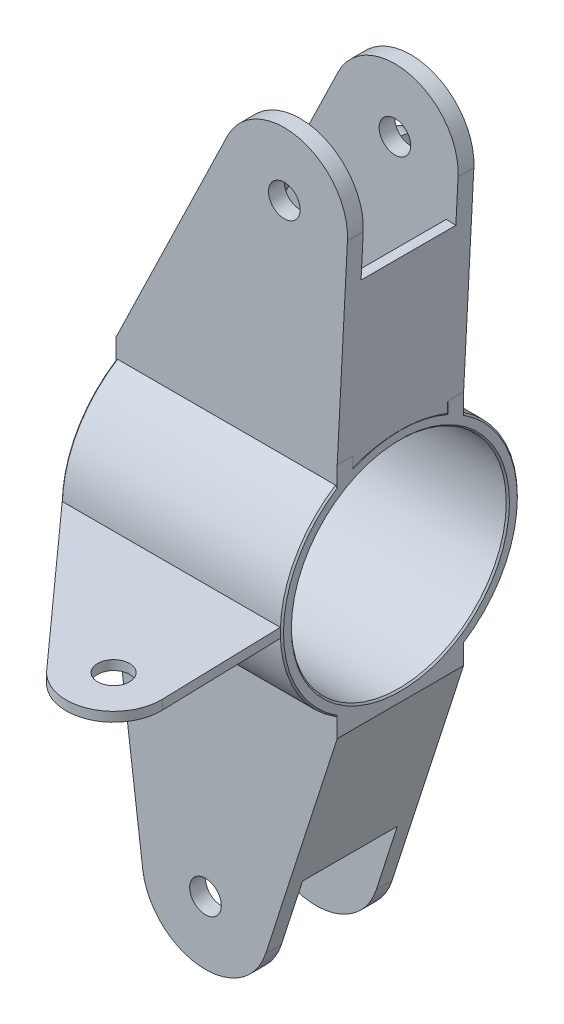
SolidWorks part; units mm, degrees
ref_plane "Front Plane" through (0, 0, 0) normal (0, 0, 1) x (1, 0, 0)
ref_plane "Top Plane" through (0, 0, 0) normal (0, 1, 0) x (1, 0, 0)
ref_plane "Right Plane" through (0, 0, 0) normal (1, 0, 0) x (0, 0, -1)
sketch "Sketch1" plane through (0, 0, 0) normal (1, 0, 0) x (0, 0, -1)
  circle A0 centre (0, 0) radius 34.007
  circle A1 centre (0, 0) radius 37.5
  dimension "D1" = 68.014
  dimension "D2" = 75
extrude "Boss-Extrude1" add sketch "Sketch1" along normal mid plane 70
sketch "Sketch4" plane through (0, 0, 0) normal (0, 0, 1) x (1, 0, 0)
  line L0 (-35, 0) -> (5.8, 0) construction
  line L1 (-35, 37.5) -> (-35, -37.5) construction
  line L2 (5.8, 101.6) -> (5.8, -101.6) construction
  line L3 (18.2749, 101.6) -> (-6.6749, -101.6) construction
  line L4 (0.2757, 110.3193) -> (-35, 37.5)
  line L5 (35, 37.5) -> (38.2484, 100.5713)
  line L6 (-35, -37.5) -> (-26.5147, -104.1267)
  line L7 (35, -37.5) -> (12.3606, -107.7358)
  line L8 (-35, -37.5) -> (35, -37.5) construction
  line L9 (-35, -37.5) -> (35, -37.5)
  line L10 (35, 37.5) -> (-35, 37.5) construction
  line L11 (35, 37.5) -> (-35, 37.5)
  circle A0 centre (18.2749, 101.6) radius 5.007
  circle A1 centre (-6.6749, -101.6) radius 5.007
  arc A2 (38.2484, 100.5713) -> (0.2757, 110.3193) centre (18.2749, 101.6) ccw
  arc A3 (-26.5147, -104.1267) -> (12.3606, -107.7358) centre (-6.6749, -101.6) ccw
  point P7 (5.8, 0)
  point P11 (5.8, 0)
  dimension "D4" = 10.014
  dimension "D5" = 203.2
  dimension "D2" = 20
  dimension "D1" = 40.8
  dimension "D3" = 7
extrude "Boss-Extrude2" add sketch "Sketch4" along normal blind 5 from offset 15 separate body
sketch "Sketch5" plane through (0, 0, 0) normal (0, 0, 1) x (1, 0, 0)
  line L0 (35, -37.5) -> (-35, -37.5) construction
  line L1 (-35, -37.5) -> (-26.5147, -104.1267) construction
  line L2 (12.3606, -107.7358) -> (35, -37.5) construction
  line L3 (35, 37.5) -> (38.2484, 100.5713) construction
  line L4 (-35, 37.5) -> (35, 37.5) construction
  line L5 (0.2757, 110.3193) -> (-35, 37.5) construction
  line L6 (35, -37.5) -> (-35, -37.5)
  line L7 (-35, -37.5) -> (-26.5147, -104.1267)
  line L8 (12.3606, -107.7358) -> (35, -37.5)
  line L9 (35, 37.5) -> (38.2484, 100.5713)
  line L10 (-35, 37.5) -> (35, 37.5)
  line L11 (0.2757, 110.3193) -> (-35, 37.5)
  arc A0 (-26.5147, -104.1267) -> (12.3606, -107.7358) centre (-6.6749, -101.6) ccw construction
  circle A1 centre (-6.6749, -101.6) radius 5.007 construction
  circle A2 centre (18.2749, 101.6) radius 5.007 construction
  arc A3 (38.2484, 100.5713) -> (0.2757, 110.3193) centre (18.2749, 101.6) ccw construction
  arc A4 (-26.5147, -104.1267) -> (12.3606, -107.7358) centre (-6.6749, -101.6) ccw
  circle A5 centre (-6.6749, -101.6) radius 5.007
  circle A6 centre (18.2749, 101.6) radius 5.007
  arc A7 (38.2484, 100.5713) -> (0.2757, 110.3193) centre (18.2749, 101.6) ccw
extrude "Boss-Extrude3" add sketch "Sketch5" against normal blind 5 from offset 15 separate body offset against normal yes
sketch "Sketch6" plane through (35, 0, 0) normal (1, 0, 0) x (0, 0, -1)
  line L0 (20, -37.5) -> (15, -37.5) construction
  line L1 (-20, -37.5) -> (-15, -37.5) construction
  line L2 (20, 37.5) -> (15, 37.5) construction
  line L3 (-20, 37.5) -> (-15, 37.5) construction
  line L4 (20, -37.5) -> (15, -37.5)
  line L5 (-20, -37.5) -> (-15, -37.5)
  line L6 (20, 37.5) -> (15, 37.5)
  line L7 (-20, 37.5) -> (-15, 37.5)
  line L8 (-20, 37.5) -> (-20, 31.7214)
  line L9 (-15, 37.5) -> (-15, 34.3693)
  line L10 (15, 37.5) -> (15, 34.3693)
  line L11 (20, 37.5) -> (20, 31.7214)
  line L12 (-20, -37.5) -> (-20, -31.7214)
  line L13 (-15, -37.5) -> (-15, -34.3693)
  line L14 (15, -37.5) -> (15, -34.3693)
  line L15 (20, -37.5) -> (20, -31.7214)
  circle A0 centre (0, 0) radius 37.5 construction
  arc A1 (-20, -31.7214) -> (-15, -34.3693) centre (0, 0) ccw
  arc A2 (-15, 34.3693) -> (-20, 31.7214) centre (0, 0) ccw
  arc A3 (20, 31.7214) -> (15, 34.3693) centre (0, 0) ccw
  arc A4 (15, -34.3693) -> (20, -31.7214) centre (0, 0) ccw
extrude "Boss-Extrude4" add sketch "Sketch6" against normal up to surface (70 mm away) up to face at (-35, 0, -37.5)
chamfer "Chamfer1" distance 0.5 angle 45 5 edges at (35, 0, -34.007) (35, 0, -37.5) (35, 37.5, 0) (35, 0, 37.5) (35, -37.5, 0)
chamfer "Chamfer2" distance 0.5 angle 45 5 edges at (-35, 0, -37.5) (-35, -37.5, 0) (-35, 0, 37.5) (-35, 37.5, 0) (-35, 0, -34.007)
sketch "Sketch12" plane through (32.9811, -1.6987, 0) normal (0.9987, -0.0514, 0) x (0, 0, -1)
  line L0 (-15, 39.2506) -> (-15, 102.4055) construction
  line L1 (-15, 35.5786) -> (-15, 39.2506) construction
  line L2 (15, 39.2506) -> (15, 35.5786) construction
  line L3 (15, 39.2506) -> (15, 102.4055) construction
  line L4 (-15, 39.2506) -> (-15, 88.7513)
  line L5 (-15, 35.5786) -> (-15, 39.2506)
  line L6 (15, 39.2506) -> (15, 35.5786)
  line L7 (15, 39.2506) -> (15, 88.7513)
  line L8 (-15, 88.7513) -> (15, 88.7513)
  ellipse E0 centre (0, 1.8003) end of major axis (37, 1.8003) minor radius 36.951 (15, 35.5786) -> (-15, 35.5786) ccw construction
  ellipse E1 centre (0, 1.8003) end of major axis (37, 1.8003) minor radius 36.951 (15, 35.5786) -> (-15, 35.5786) ccw
  dimension "D1" = 50
extrude "Boss-Extrude8" add sketch "Sketch12" against normal blind 3
sketch "Sketch13" plane through (-43.0609, 20.8599, 0) normal (-0.9, 0.436, 0) x (0, 0, 1)
  line L0 (15, 99.4035) -> (15, 18.4898) construction
  line L1 (-15, 99.4035) -> (-15, 18.4898) construction
  line L2 (15, 73.4898) -> (15, 18.4898)
  line L3 (-15, 73.4898) -> (-15, 18.4898)
  line L4 (-15, 18.4898) -> (15, 18.4898)
  line L5 (-15, 73.4898) -> (15, 73.4898)
  dimension "D1" = 55
extrude "Boss-Extrude9" add sketch "Sketch13" against normal blind 3
sketch "Sketch14" plane through (-35, 0, 0) normal (-1, 0, 0) x (0, 0, 1)
  line L0 (15, 37.5) -> (15, 33.8231) construction
  line L1 (-15, 33.8231) -> (-15, 37.5) construction
  line L2 (-15, 37.5) -> (15, 37.5) construction
  line L3 (15, 37.5) -> (15, 33.8231)
  line L4 (-15, 33.8231) -> (-15, 37.5)
  line L5 (-15, 37.5) -> (15, 37.5)
  arc A0 (15, 33.8231) -> (-15, 33.8231) centre (0, 0) ccw construction
  arc A1 (15, 33.8231) -> (-15, 33.8231) centre (0, 0) ccw
extrude "Boss-Extrude10" add sketch "Sketch14" against normal blind 3
sketch "Sketch15" plane through (-39.141, -4.9849, 0) normal (-0.992, -0.1263, 0) x (0, 0, 1)
  line L0 (15, -32.7778) -> (15, -99.9427) construction
  line L1 (-15, -32.7778) -> (-15, -99.9427) construction
  line L2 (15, -32.7778) -> (15, -82.7778)
  line L3 (-15, -32.7778) -> (-15, -82.7778)
  line L4 (-15, -32.7778) -> (15, -32.7778)
  line L6 (-15, -82.7778) -> (15, -82.7778)
  dimension "D1" = 50
extrude "Boss-Extrude11" add sketch "Sketch15" against normal blind 3
sketch "Sketch16" plane through (-35, 0, 0) normal (-1, 0, 0) x (0, 0, 1)
  line L0 (15, -37.5) -> (-15, -37.5) construction
  line L1 (15, -33.8231) -> (15, -37.5) construction
  line L2 (-15, -37.5) -> (-15, -33.8231) construction
  line L3 (15, -37.5) -> (-15, -37.5)
  line L4 (15, -33.8231) -> (15, -37.5)
  line L5 (-15, -37.5) -> (-15, -33.8231)
  arc A0 (-15, -33.8231) -> (15, -33.8231) centre (0, 0) ccw construction
  arc A1 (-15, -33.8231) -> (15, -33.8231) centre (0, 0) ccw
extrude "Boss-Extrude12" add sketch "Sketch16" against normal blind 3
sketch "Sketch17" plane through (42.6556, -13.7493, 0) normal (0.9518, -0.3068, 0) x (0, 0, -1)
  line L0 (-15, -98.7484) -> (-15, -24.954) construction
  line L1 (15, -98.7484) -> (15, -24.954) construction
  line L2 (-15, -76.954) -> (-15, -24.954)
  line L3 (15, -76.954) -> (15, -24.954)
  line L4 (-15, -24.954) -> (15, -24.954)
  line L6 (-15, -76.954) -> (15, -76.954)
  dimension "D1" = 52
extrude "Boss-Extrude13" add sketch "Sketch17" against normal blind 3
sketch "Sketch19" plane through (35, 0, 0) normal (1, 0, 0) x (0, 0, -1)
  line L1 (15, -37.5) -> (-15, -37.5) construction
  line L2 (-15, -37.5) -> (-15, -33.8231) construction
  line L3 (15, -33.8231) -> (15, -37.5) construction
  line L4 (-15, -37.5) -> (-15, -33.8231)
  line L5 (15, -33.8231) -> (15, -37.5)
  line L6 (15, -37.5) -> (-15, -37.5)
  arc A0 (-15, -33.8231) -> (15, -33.8231) centre (0, 0) ccw construction
  arc A1 (-15, -33.8231) -> (15, -33.8231) centre (0, 0) ccw
extrude "Boss-Extrude14" add sketch "Sketch19" against normal blind 3
sketch "Sketch22" plane through (0, 0, 0) normal (0, 1, 0) x (1, 0, 0)
  line L0 (0, 0) -> (0, -87.1809) construction
  line L1 (0, 0) -> (20.5384, -76.2773) construction
  line L2 (-34.5, -37.5) -> (34.5, -37.5) construction
  line L3 (-34.5, -37.5) -> (34.5, -37.5)
  line L4 (34.5, -37.5) -> (35.5329, -75.8737)
  line L5 (-34.5, -37.5) -> (9.3842, -86.3065)
  circle A0 centre (20.5384, -76.2773) radius 5.05
  arc A1 (9.3842, -86.3065) -> (35.5329, -75.8737) centre (20.5384, -76.2773) ccw
  dimension "D4" = 10.1
  dimension "D5" = 30
  dimension "D1" = 87.1809
  dimension "D2" = 15.07
  dimension "D3" = 78.994
extrude "Boss-Extrude16" add sketch "Sketch22" along normal mid plane 3 separate body
ref_plane "Plane1" through (-25.9, 0, 0) normal (-1, 0, 0) x (0, 0, 1)
sketch "Sketch23" plane through (-25.9, 0, 0) normal (-1, 0, 0) x (0, 0, 1)
  line L0 (0, 0) -> (-37.5, 0) construction
  line L1 (0, 0) -> (0, 120.461) construction
  line L2 (0, 0) -> (-56.4709, 50.6685) construction
  line L3 (-20, 31.7214) -> (-49.8402, 58.154)
  line L4 (-37.5, 0) -> (-65.0266, 45.4915)
  arc A0 (-20, 31.7214) -> (-20, -31.7214) centre (0, 0) ccw construction
  circle A1 centre (0, 0) radius 75.87 construction
  circle A2 centre (-56.4709, 50.6685) radius 3
  arc A3 (-49.8402, 58.154) -> (-65.0266, 45.4915) centre (-56.4709, 50.6685) ccw
  arc A4 (-20, 31.7214) -> (-37.5, 0) centre (0, 0) ccw
  dimension "D1" = 151.74
  dimension "D3" = 6
  dimension "D4" = 20
  dimension "D2" = 48.1
extrude "Boss-Extrude17" add sketch "Sketch23" against normal blind 4
